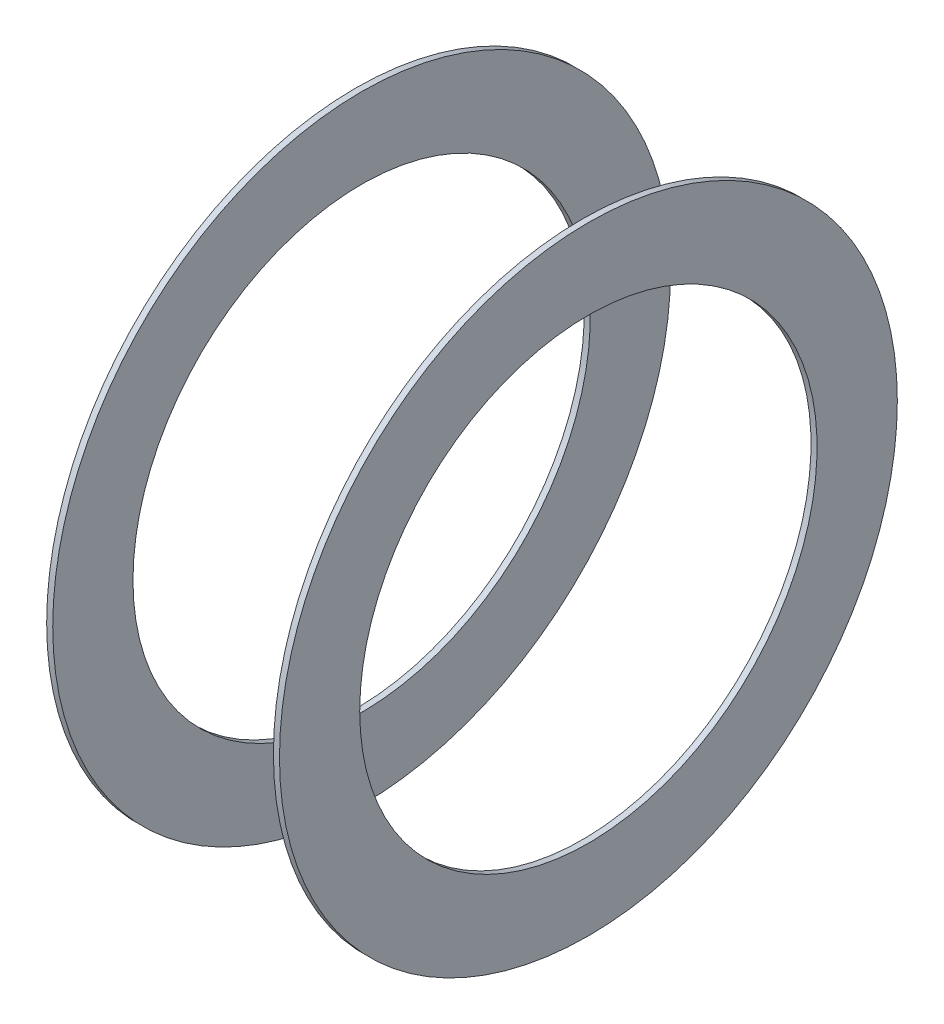
SolidWorks part; units mm, degrees
ref_plane "Plan de face" through (0, 0, 0) normal (0, 0, 1) x (1, 0, 0)
ref_plane "Plan de dessus" through (0, 0, 0) normal (0, 1, 0) x (1, 0, 0)
ref_plane "Plan de droite" through (0, 0, 0) normal (1, 0, 0) x (0, 0, -1)
sketch "Esquisse1" plane through (0, 0, 0) normal (0, 0, 1) x (1, 0, 0)
  line L0 (15.6319, 11.6379) -> (15.6319, -0.4348) construction
  line L1 (19.1319, -10.5) -> (19.1319, 10.5) construction
  line L2 (12.3147, -8.804) -> (12.3147, 8.804) construction
  line L3 (12.3147, 6.5171) -> (12.4875, 6.5171)
  line L4 (12.3147, 6.5171) -> (12.3147, 8.804)
  line L5 (12.3147, 8.804) -> (12.4875, 8.804)
  line L6 (12.4875, 6.5171) -> (12.4875, 8.804)
  line L7 (12.4875, 8.804) -> (12.4875, -8.804) construction
  line L8 (18.7764, 6.5171) -> (18.7764, 8.804)
  line L9 (18.9492, 8.804) -> (18.7764, 8.804)
  line L10 (18.9492, 6.5171) -> (18.9492, 8.804)
  line L11 (18.9492, 6.5171) -> (18.7764, 6.5171)
  line L12 (10.7456, 0) -> (20.1392, 0) construction
  line L13 (8.8007, 0) -> (22.3746, 0) construction
  dimension "D1" = 3.5
revolve "Révolution1" add sketch "Esquisse1" angle 360 about L12
